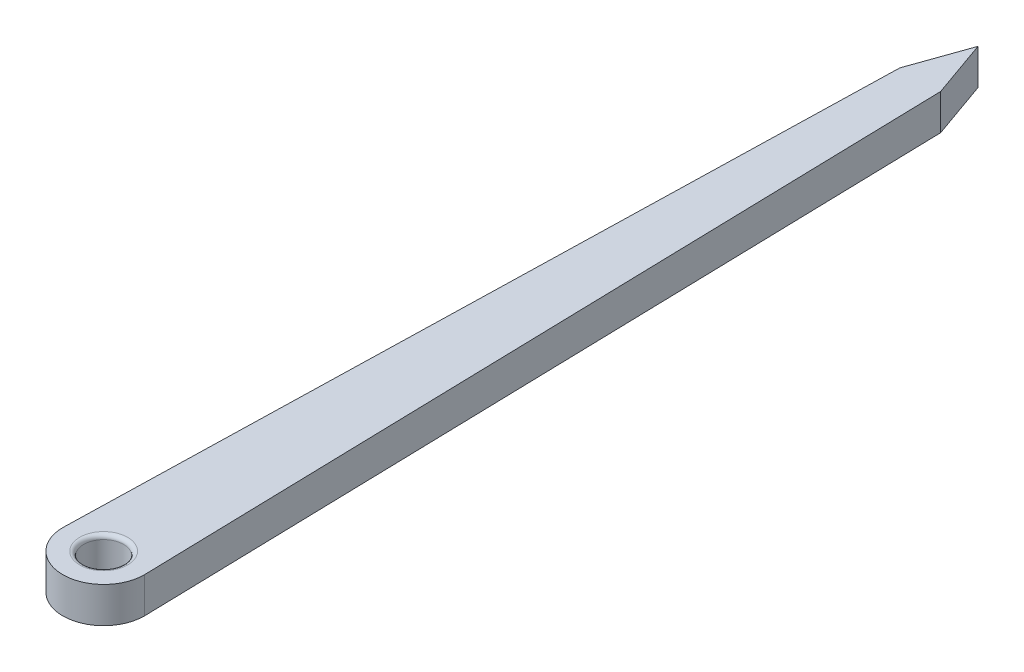
SolidWorks part; units mm, degrees
ref_plane "Přední rovina" through (0, 0, 0) normal (0, 0, 1) x (1, 0, 0)
ref_plane "Horní rovina" through (0, 0, 0) normal (0, 1, 0) x (1, 0, 0)
ref_plane "Pravá rovina" through (0, 0, 0) normal (1, 0, 0) x (0, 0, -1)
sketch "Skica1" plane through (0, 0, 0) normal (0, 1, 0) x (1, 0, 0)
  line L0 (-4, 0) -> (-2, 80)
  line L1 (-2, 80) -> (0, 85.6569)
  line L2 (0, 85.6569) -> (2, 80)
  line L3 (2, 80) -> (4, 0)
  circle A4 centre (0, 0) radius 4
  circle A5 centre (0, 0) radius 1.75
  dimension "D1" = 8
  dimension "D2" = 3.5
  dimension "D7" = 4
  dimension "D8" = 80
  dimension "D3" = 0
  dimension "D4" = 6
  dimension "D5" = 6
  dimension "D6" = 80
extrude "Přidat vysunutím1" add sketch "Skica1" along normal blind 3.5 contours A4 L3 L2 L1 L0 | L3 A4 L0 A5
sketch "Skica2" plane through (0, 3.5, 0) normal (0, 1, 0) x (1, 0, 0)
  circle A1 centre (0, 0) radius 1.95
  dimension "D1" = 3.9
extrude "Odebrat vysunutím1" cut sketch "Skica2" against normal blind 100
fillet "Zaoblit1" radius 0.4 1 edges at (0, 3.5, 1.95)
